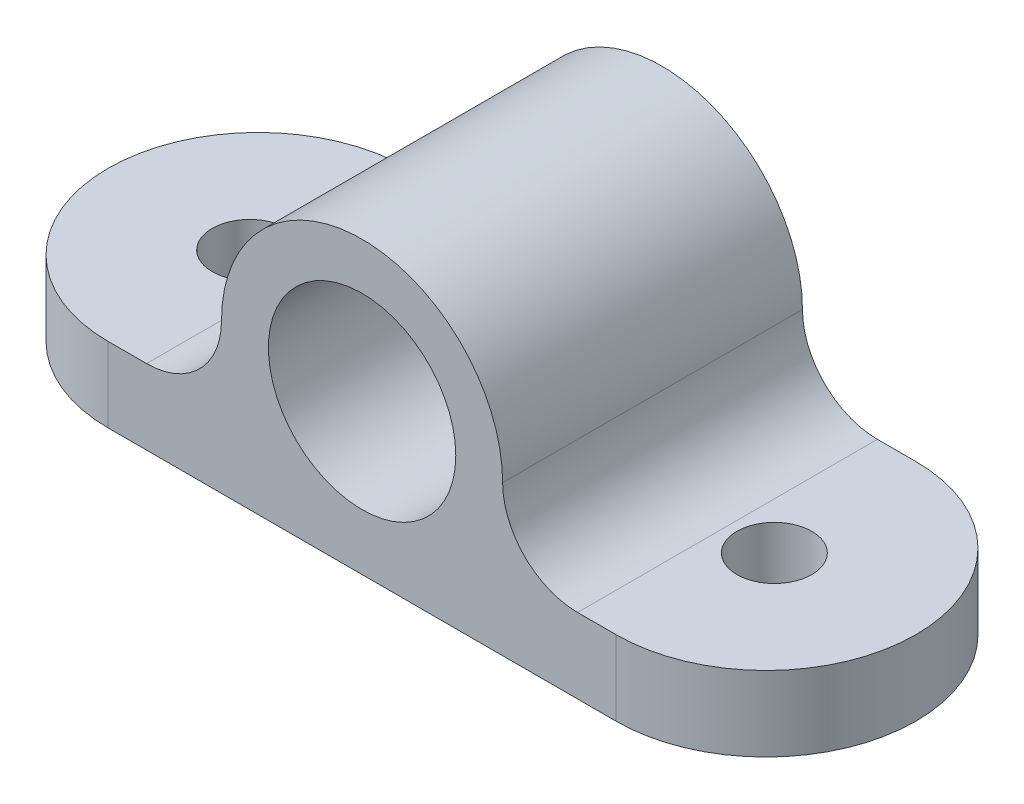
SolidWorks part; units mm, degrees
ref_plane "Front Plane" through (0, 0, 0) normal (0, 0, 1) x (1, 0, 0)
ref_plane "Top Plane" through (0, 0, 0) normal (0, 1, 0) x (1, 0, 0)
ref_plane "Right Plane" through (0, 0, 0) normal (1, 0, 0) x (0, 0, -1)
sketch "Sketch1" plane through (0, 0, 0) normal (0, 0, 1) x (1, 0, 0)
  line L0 (-107.7686, 0) -> (107.7686, 0)
  line L1 (107.7686, 0) -> (107.7686, 20)
  line L3 (-107.7686, 20) -> (-107.7686, 0)
  line L4 (107.7686, 20) -> (57.5, 20)
  line L5 (-57.5, 20) -> (-107.7686, 20)
  circle A0 centre (0, 40) radius 25
  arc A1 (37.5, 40) -> (-37.5, 40) centre (0, 40) ccw
  arc A2 (37.5, 40) -> (57.5, 20) centre (57.5, 40) ccw
  arc A3 (-37.5, 40) -> (-57.5, 20) centre (-57.5, 40) cw
  point P0 (107.7686, 20)
  point P4 (0, 0)
  point P10 (0, 40)
  point P17 (37.5, 40)
  point P20 (-37.5, 40)
  dimension "D4" = 20
  dimension "D1" = 20
  dimension "D2" = 40
extrude "Boss-Extrude1" add sketch "Sketch1" against normal blind 80
sketch "Sketch2" plane through (0, 20, 0) normal (0, 1, 0) x (1, 0, 0)
  line L0 (107.7686, 0) -> (57.5, 0) construction
  line L1 (107.7686, 80) -> (107.7686, 0) construction
  line L2 (107.7686, 80) -> (57.5, 80) construction
  line L3 (67.7686, 80) -> (67.7686, 0)
  line L4 (-107.7686, 80) -> (-107.7686, 0) construction
  line L5 (-57.5, 0) -> (-107.7686, 0) construction
  line L6 (-57.5, 80) -> (-107.7686, 80) construction
  line L7 (-67.7686, 80) -> (-67.7686, 0)
  line L8 (-67.7686, 0) -> (-107.7686, 0)
  line L9 (-107.7686, 0) -> (-107.7686, 80)
  line L10 (-107.7686, 80) -> (-67.7686, 80)
  line L11 (-107.7686, 80) -> (-67.7686, 80)
  line L12 (67.7686, 80) -> (107.7686, 80)
  line L13 (107.7686, 80) -> (107.7686, 0)
  line L14 (107.7686, 0) -> (67.7686, 0)
  arc A0 (67.7686, 80) -> (67.7686, 0) centre (67.7686, 40) cw
  arc A1 (-67.7686, 80) -> (-67.7686, 0) centre (-67.7686, 40) ccw
  point P0 (67.7686, 40)
  point P10 (-67.7686, 40)
  line M3 (57.5, 0) -> (107.7686, 0)
  line M4 (107.7686, 0) -> (107.7686, 80)
  line M5 (107.7686, 80) -> (57.5, 80)
  dimension "D1" = 40
  dimension "D2" = 40
  dimension "D3" = 40
  dimension "D4" = 40
extrude "Cut-Extrude1" cut sketch "Sketch2" against normal blind 80 contours A1 L9 L8 | A1 L10 L9 | A0 M4 M3 | A0 L13 M5
sketch "Sketch3" plane through (0, 20, 0) normal (0, 1, 0) x (1, 0, 0)
  line L1 (67.7686, 80) -> (57.5, 80) construction
  line L3 (-57.5, 0) -> (-67.7686, 0) construction
  circle A0 centre (70, 40) radius 10
  circle A1 centre (-70, 40) radius 10
  point P2 (70.2536, 39.6697)
  point P3 (0, 0)
  point P4 (57.5, 40)
  point P5 (57.5, 40)
  point P11 (-78.1819, 40)
  dimension "D1" = 70
  dimension "D3" = 40
  dimension "D2" = 40
  dimension "D4" = 70
extrude "Cut-Extrude2" cut sketch "Sketch3" against normal blind 80
